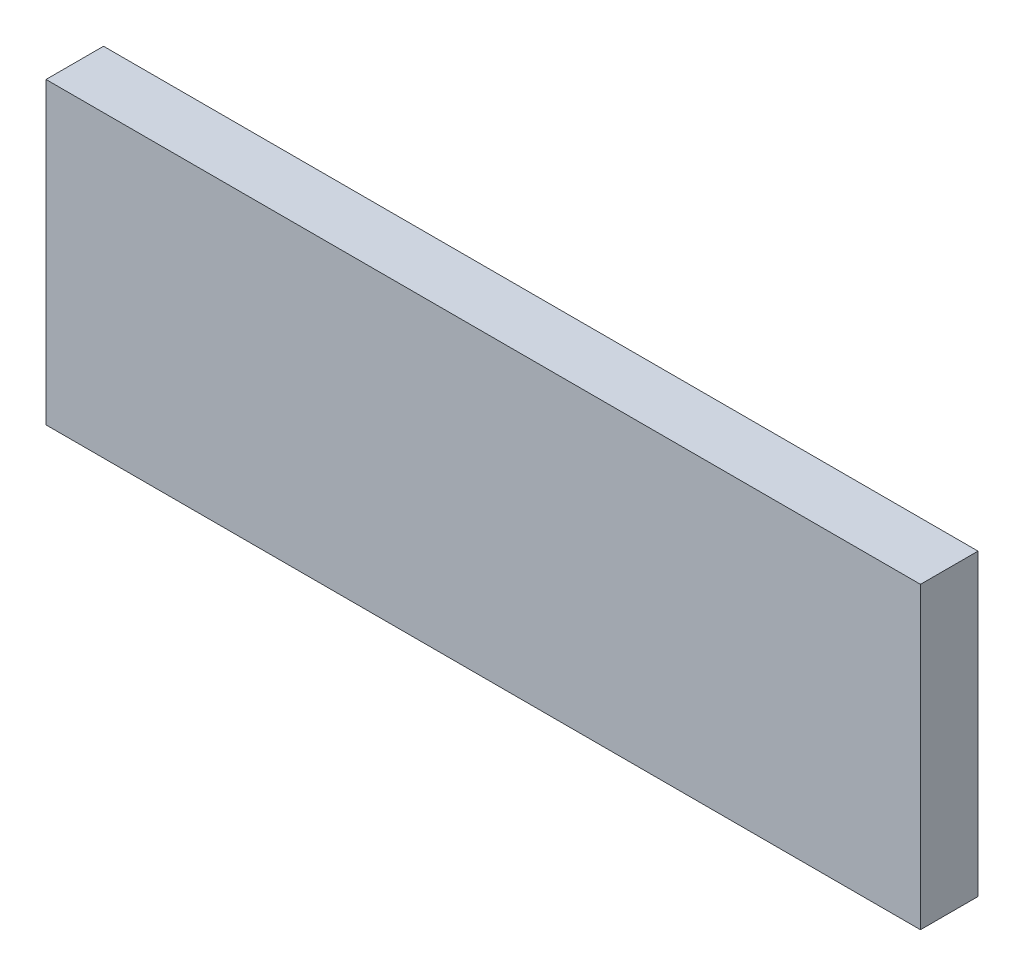
SolidWorks part; units mm, degrees
ref_plane "Plan de face" through (0, 0, 0) normal (0, 0, 1) x (1, 0, 0)
ref_plane "Plan de dessus" through (0, 0, 0) normal (0, 1, 0) x (1, 0, 0)
ref_plane "Plan de droite" through (0, 0, 0) normal (1, 0, 0) x (0, 0, -1)
sketch "Esquisse1" plane through (0, 0, 0) normal (0, 0, 1) x (1, 0, 0)
  line L1 (-152, -52) -> (152, -52)
  line L2 (-152, -52) -> (-152, 52)
  line L3 (-152, 52) -> (152, 52)
  line L4 (152, -52) -> (152, 52)
  line L5 (-152, -52) -> (152, 52) construction
  line L6 (-152, 52) -> (152, -52) construction
  point P0 (0, 0)
  dimension "D1" = 104
  dimension "D2" = 304
extrude "Boss.-Extru.1" add sketch "Esquisse1" along normal blind 20
